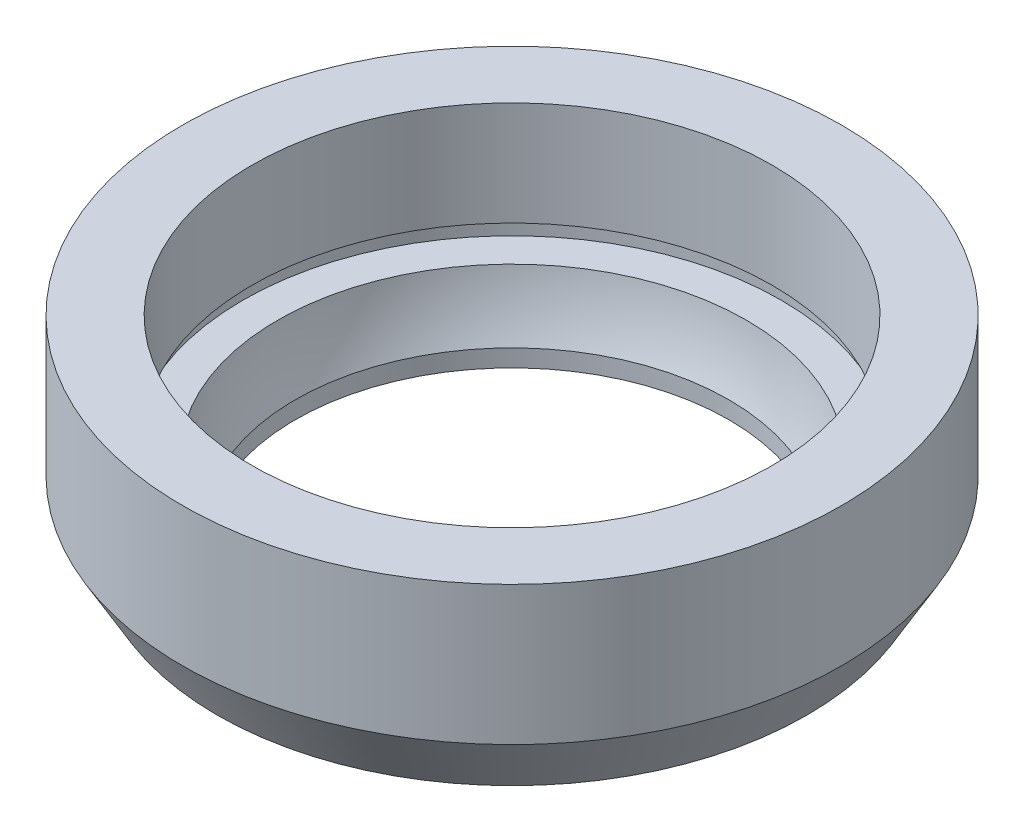
SolidWorks part; units mm, degrees
ref_plane "Plan de face" through (0, 0, 0) normal (0, 0, 1) x (1, 0, 0)
ref_plane "Plan de dessus" through (0, 0, 0) normal (0, 1, 0) x (1, 0, 0)
ref_plane "Plan de droite" through (0, 0, 0) normal (1, 0, 0) x (0, 0, -1)
sketch "Esquisse1" plane through (0, 0, 0) normal (0, 0, 1) x (1, 0, 0)
  line L0 (0, -202.9346) -> (0, 145.2111) construction
  line L1 (0, -186.153) -> (170, -186.153)
  line L2 (170, -186.153) -> (190, -151.512)
  line L3 (190, -151.512) -> (0, -151.512)
  line L4 (0, -151.512) -> (0, -186.153)
  line L5 (190, -151.512) -> (190, -71.512)
  line L6 (190, -71.512) -> (0, -71.512)
  line L7 (0, -71.512) -> (0, -151.512)
  line L8 (125, -186.153) -> (125, -176.153)
  line L9 (125, -176.153) -> (0, -176.153)
  line L10 (0, -141.512) -> (155.15, -141.512)
  line L11 (155.15, -141.512) -> (155.15, -131.512)
  line L12 (155.15, -131.512) -> (0, -131.512)
  line L13 (150, -131.512) -> (150, -71.512)
  arc A0 (125, -176.153) -> (135.15, -141.512) centre (0.8523, -120.9696) ccw
  point P14 (135.15, -141.512)
  dimension "D12" = 271.7195
  dimension "D1" = 202.9346
  dimension "D2" = 170
  dimension "D3" = 190
  dimension "D4" = 151.512
  dimension "D5" = 60
  dimension "D6" = 80
  dimension "D7" = 45
  dimension "D8" = 10
  dimension "D9" = 10
  dimension "D10" = 20
  dimension "D11" = 155.15
  dimension "D13" = 60
  dimension "D14" = 40
revolve "Révolution1" add sketch "Esquisse1" angle 360 about L0
